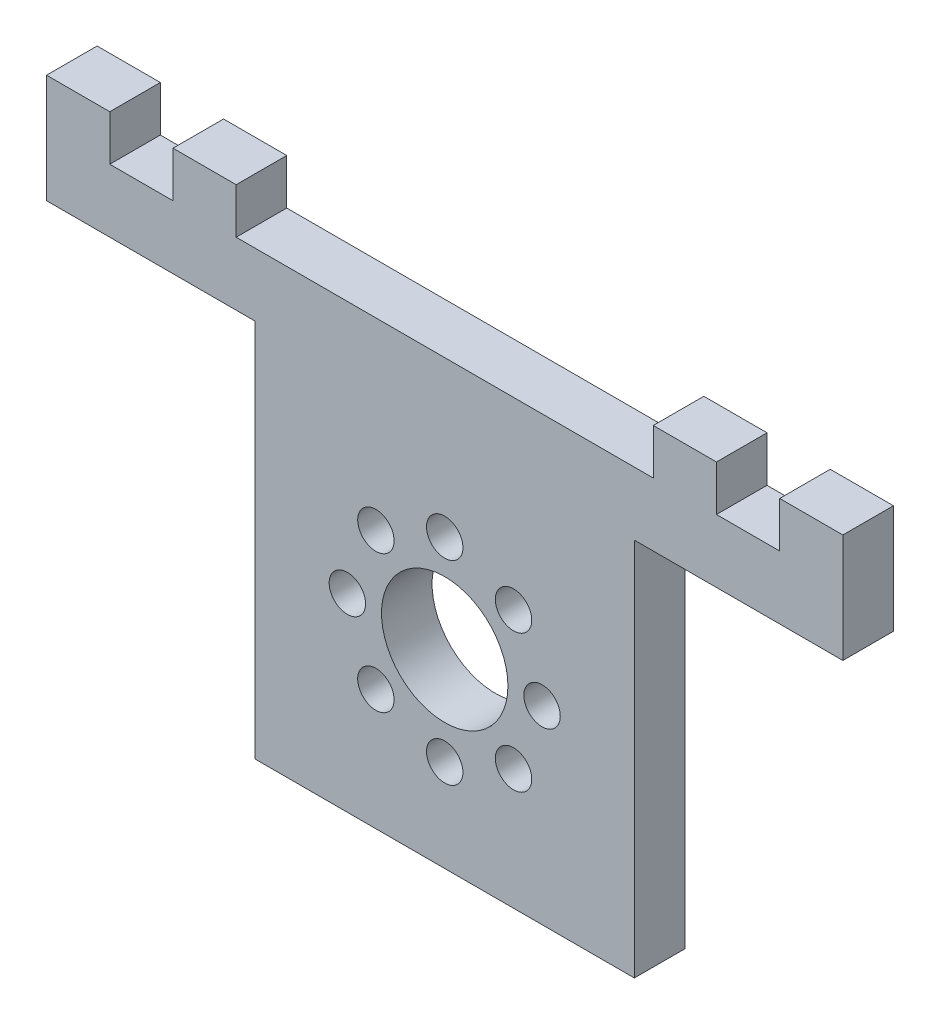
SolidWorks part; units mm, degrees
ref_plane "Front Plane" through (0, 0, 0) normal (0, 0, 1) x (1, 0, 0)
ref_plane "Top Plane" through (0, 0, 0) normal (0, 1, 0) x (1, 0, 0)
ref_plane "Right Plane" through (0, 0, 0) normal (1, 0, 0) x (0, 0, -1)
sketch "Sketch1" plane through (0, 0, 0) normal (0, 0, 1) x (1, 0, 0)
  line L0 (-22.9195, 7.5902) -> (-22.9195, 1.2402)
  line L1 (-22.9195, 1.2402) -> (-1.9696, 1.2402)
  line L2 (-1.9696, 1.2402) -> (-1.9696, -36.8598)
  line L3 (-1.9696, -36.8598) -> (36.1304, -36.8598)
  line L4 (36.1304, -36.8598) -> (36.1304, 1.2402)
  line L5 (36.1304, 1.2402) -> (57.0803, 1.2402)
  line L6 (57.0803, 1.2402) -> (57.0803, 7.5902)
  line L7 (57.0803, 7.5902) -> (-22.9195, 7.5902)
  dimension "D1" = 6.35
  dimension "D2" = 38.1
  dimension "D3" = 6.35
  dimension "D4" = 20.9499
  dimension "D5" = 20.9499
  dimension "D6" = 38.1
extrude "Boss-Extrude1" add sketch "Sketch1" along normal blind 5.08
sketch "Sketch3" plane through (0, 0, 0) normal (0, 0, -1) x (-1, 0, 0)
  line L0 (-57.0803, 7.5902) -> (22.9195, 7.5902) construction
  line L1 (22.9195, 7.5902) -> (16.5695, 7.5902)
  line L2 (22.9195, 7.5902) -> (22.9195, 12.1622)
  line L3 (22.9195, 12.1622) -> (16.5695, 12.1622)
  line L4 (16.5695, 7.5902) -> (16.5695, 12.1622)
  line L5 (10.2195, 7.5902) -> (3.8695, 7.5902)
  line L6 (10.2195, 7.5902) -> (10.2195, 12.1622)
  line L7 (10.2195, 12.1622) -> (3.8695, 12.1622)
  line L8 (3.8695, 7.5902) -> (3.8695, 12.1622)
  line L9 (-17.0804, -36.8598) -> (-17.0804, 44.4444) construction
  line L10 (-2.4805, 7.5902) -> (-8.8305, 7.5902)
  line L11 (-2.4805, 7.5902) -> (-2.4805, 12.1622)
  line L12 (-2.4805, 12.1622) -> (-8.8305, 12.1622)
  line L13 (-8.8305, 7.5902) -> (-8.8305, 12.1622)
  line L14 (1.9696, -36.8598) -> (-36.1304, -36.8598) construction
  line L15 (-25.3303, 7.5902) -> (-25.3303, 12.1622)
  line L16 (-31.6803, 12.1622) -> (-25.3303, 12.1622)
  line L17 (-31.6803, 7.5902) -> (-31.6803, 12.1622)
  line L18 (-31.6803, 7.5902) -> (-25.3303, 7.5902)
  line L19 (-38.0303, 7.5902) -> (-38.0303, 12.1622)
  line L20 (-44.3803, 12.1622) -> (-38.0303, 12.1622)
  line L21 (-44.3803, 7.5902) -> (-44.3803, 12.1622)
  line L22 (-44.3803, 7.5902) -> (-38.0303, 7.5902)
  line L23 (-50.7303, 7.5902) -> (-50.7303, 12.1622)
  line L24 (-57.0803, 12.1622) -> (-50.7303, 12.1622)
  line L25 (-57.0803, 7.5902) -> (-57.0803, 12.1622)
  line L26 (-57.0803, 7.5902) -> (-50.7303, 7.5902)
  dimension "D1" = 6.35
  dimension "D2" = 6.35
  dimension "D3" = 6.35
  dimension "D4" = 4.572
  dimension "D5" = 4.572
  dimension "D6" = 4.572
  dimension "D7" = 6.35
  dimension "D8" = 6.35
extrude "Boss-Extrude2" add sketch "Sketch3" against normal blind 5.08
sketch "Sketch4" plane through (0, 0, 5.08) normal (0, 0, 1) x (1, 0, 0)
  line L0 (-1.9696, -17.8098) -> (36.1304, -17.8098) construction
  line L1 (-1.9696, 1.2402) -> (-1.9696, -36.8598) construction
  line L2 (36.1304, -36.8598) -> (36.1304, 1.2402) construction
  line L3 (17.0804, -36.8598) -> (17.0804, 7.5902) construction
  line L4 (-1.9696, -36.8598) -> (36.1304, -36.8598) construction
  line L5 (25.3303, 7.5902) -> (8.8305, 7.5902) construction
  circle A0 centre (17.0804, -17.8098) radius 6.35
  circle A1 centre (7.3014, -17.8098) radius 1.8288
  circle A2 centre (10.1656, -10.895) radius 1.8288
  circle A3 centre (17.0804, -8.0308) radius 1.8288
  circle A4 centre (23.9952, -10.895) radius 1.8288
  circle A5 centre (26.8594, -17.8098) radius 1.8288
  circle A6 centre (23.9952, -24.7246) radius 1.8288
  circle A7 centre (17.0804, -27.5888) radius 1.8288
  circle A8 centre (10.1656, -24.7246) radius 1.8288
  point P33 (17.0804, -17.8098)
  dimension "D1" = 12.7
  dimension "D2" = 3.6576
  dimension "D3" = 9.779
  dimension "D4" = 8
extrude "Cut-Extrude1" cut sketch "Sketch4" against normal blind 5.08
sketch "Sketch5" plane through (0, 0, 5.08) normal (0, 0, 1) x (1, 0, 0)
  line L1 (2.4805, 12.1622) -> (31.6803, 12.1622)
  line L2 (2.4805, 12.1622) -> (2.4805, 7.5902)
  line L3 (2.4805, 7.5902) -> (31.6803, 7.5902)
  line L4 (31.6803, 12.1622) -> (31.6803, 7.5902)
extrude "Cut-Extrude2" cut sketch "Sketch5" against normal blind 5.08
